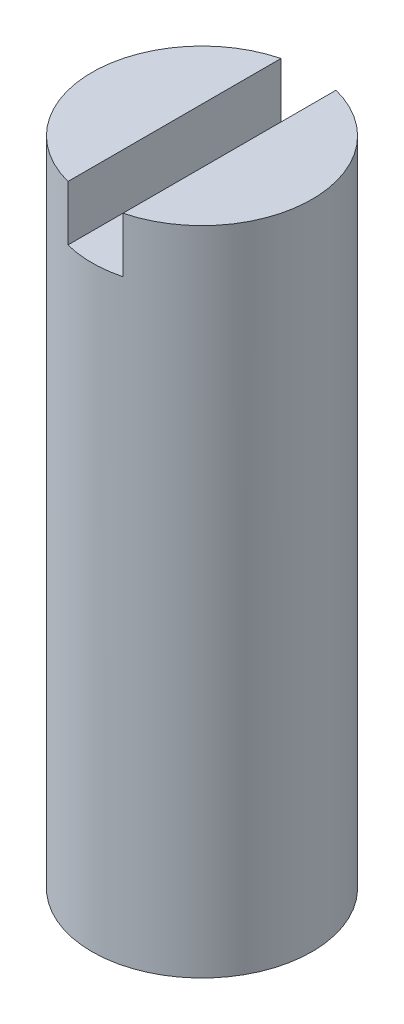
SolidWorks part; units mm, degrees
ref_plane "Front Plane" through (0, 0, 0) normal (0, 0, 1) x (1, 0, 0)
ref_plane "Top Plane" through (0, 0, 0) normal (0, 1, 0) x (1, 0, 0)
ref_plane "Right Plane" through (0, 0, 0) normal (1, 0, 0) x (0, 0, -1)
sketch "Sketch1" plane through (0, 0, 0) normal (0, 1, 0) x (1, 0, 0)
  circle A0 centre (0, 0) radius 2
  dimension "D1" = 4
extrude "Boss-Extrude1" add sketch "Sketch1" along normal blind 13
cosmetic thread "Cosmetic Thread1" parameters "D1"=8, "D2"=3.22
chamfer "Chamfer1" distance 2 angle 30 1 edges at (0, 0, 2)
sketch "Sketch2" plane through (0, 13, 0) normal (0, 1, 0) x (1, 0, 0)
  line L1 (-0.5, 2.151) -> (0.5, 2.151)
  line L2 (-0.5, 2.151) -> (-0.5, -2.3136)
  line L3 (-0.5, -2.3136) -> (0.5, -2.3136)
  line L4 (0.5, 2.151) -> (0.5, -2.3136)
  dimension "D1" = 1
  dimension "D2" = 0.5
extrude "Cut-Extrude1" cut sketch "Sketch2" against normal blind 1
